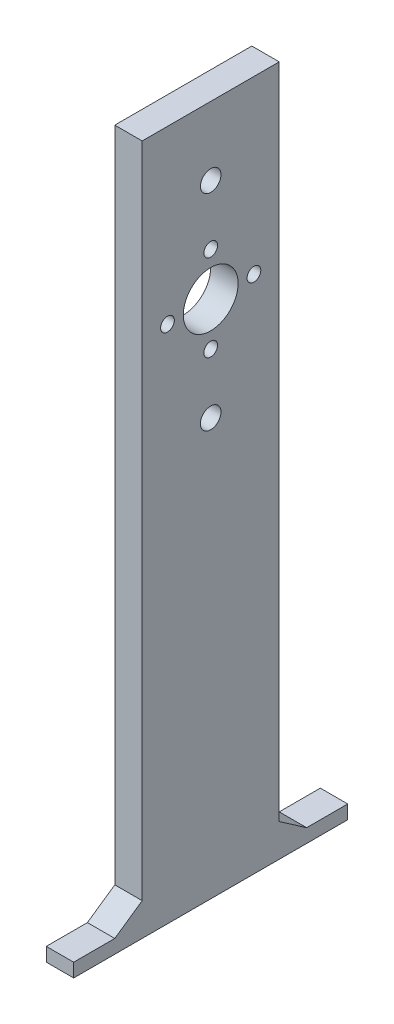
SolidWorks part; units mm, degrees
ref_plane "Front Plane" through (0, 0, 0) normal (0, 0, 1) x (1, 0, 0)
ref_plane "Top Plane" through (0, 0, 0) normal (0, 1, 0) x (1, 0, 0)
ref_plane "Right Plane" through (0, 0, 0) normal (1, 0, 0) x (0, 0, -1)
sketch "Sketch1" plane through (0, 0, 0) normal (0, 1, 0) x (1, 0, 0)
  line L1 (10, 0) -> (10, 50)
  line L2 (0, 0) -> (0, 50)
  line L4 (0, 50) -> (0, 75)
  line L5 (0, 153.69) -> (0, -246.31) construction
  line L6 (0, 75) -> (10, 75)
  line L7 (10, 75) -> (10, 50)
  line L8 (0, 0) -> (0, -25)
  line L9 (0, -25) -> (10, -25)
  line L10 (10, -25) -> (10, 0)
extrude "Boss-Extrude1" add sketch "Sketch1" along normal blind 252
sketch "Sketch3" plane through (0, 0, 0) normal (-1, 0, 0) x (0, 0, 1)
  line L0 (25, 200) -> (25, 5)
  line L2 (-75, 252) -> (25, 252) construction
  line L5 (0, 200) -> (25, 200)
  line L6 (-75, 252) -> (-75, 0) construction
  line L7 (-75, 5) -> (-60, 5)
  line L8 (-60, 5) -> (-50, 11.9378)
  line L9 (-50, 11.9378) -> (-50, 252)
  line L10 (-50, 252) -> (-75, 252)
  line L11 (-75, 252) -> (-75, 5)
  line L12 (0, 11.9378) -> (0, 200)
  line L13 (10, 5) -> (0, 11.9378)
  line L14 (25, 5) -> (10, 5)
extrude "Cut-Extrude2" cut sketch "Sketch3" against normal blind 10
sketch "Sketch4" plane through (10, 0, 0) normal (1, 0, 0) x (0, 0, -1)
  line L0 (0, 200) -> (0, 252)
  line L1 (-25, 252) -> (50, 252) construction
  line L2 (0, 252) -> (-25, 252)
  line L3 (-25, 252) -> (-25, 200)
  line L4 (-25, 200) -> (0, 200)
extrude "Cut-Extrude3" cut sketch "Sketch4" against normal blind 10
sketch "Sketch5" plane through (10, 0, 0) normal (1, 0, 0) x (0, 0, -1)
  line L0 (25, 227) -> (25, 252) construction
  line L1 (0, 252) -> (50, 252) construction
  line L2 (25, 227) -> (25, 189.5) construction
  line L3 (25, 189.5) -> (25, 152) construction
  circle A0 centre (25, 227) radius 3.75
  circle A1 centre (25, 189.5) radius 10
  circle A2 centre (25, 152) radius 3.75
  dimension "D1" = 25
  dimension "D4" = 20
  dimension "D5" = 7.5
  dimension "D6" = 7.5
  dimension "D2" = 37.5
  dimension "D3" = 37.5
extrude "Cut-Extrude5" cut sketch "Sketch5" against normal through all
sketch "Sketch6" plane through (0, 0, 0) normal (-1, 0, 0) x (0, 0, 1)
  line L0 (-25, 189.5) -> (0, 189.5) construction
  line L1 (0, 252) -> (0, 11.9378) construction
  line L2 (0, 189.5) -> (-50, 189.5) construction
  line L3 (-50, 11.9378) -> (-50, 252) construction
  line L4 (-25, 189.5) -> (-25, 163.8532) construction
  line L5 (-25, 163.8532) -> (-25, 215.9809) construction
  circle A1 centre (-40.77, 189.5) radius 2.5
  circle A2 centre (-9.23, 189.5) radius 2.5
  circle A5 centre (-25, 205.27) radius 2.5
  circle A7 centre (-25, 173.73) radius 2.5
  point P22 (0, 0)
extrude "Cut-Extrude6" cut sketch "Sketch6" against normal through all
